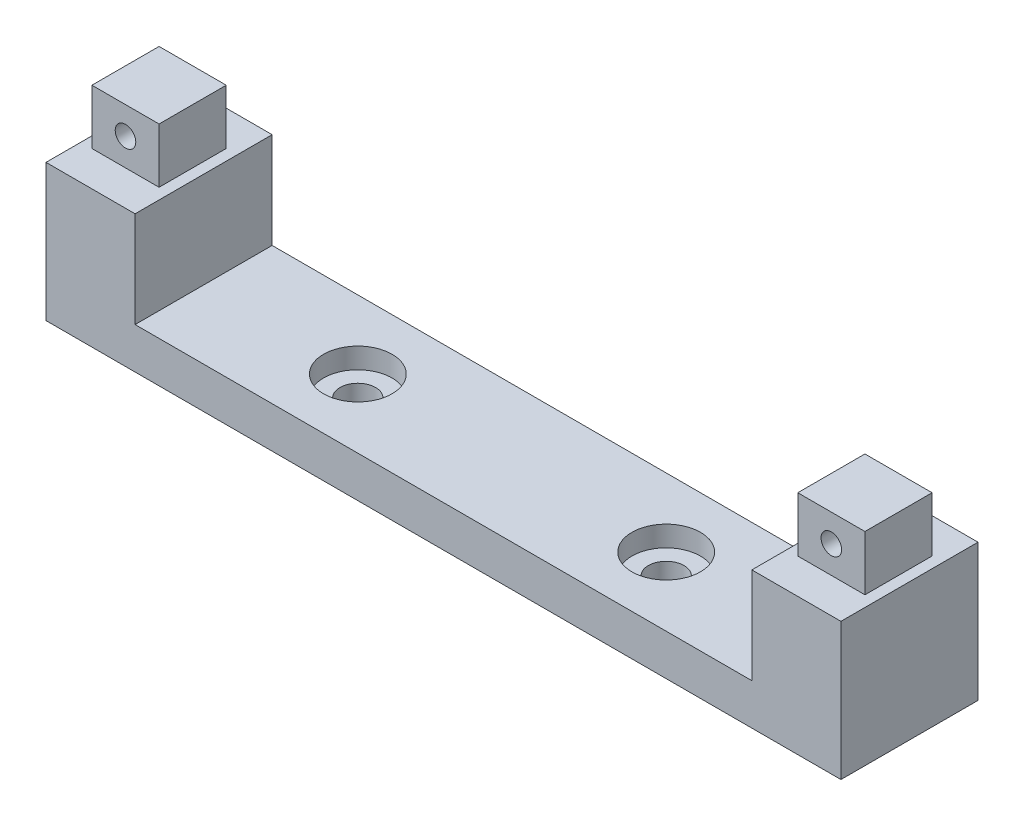
SolidWorks part; units mm, degrees
ref_plane "前视基准面" through (0, 0, 0) normal (0, 0, 1) x (1, 0, 0)
ref_plane "上视基准面" through (0, 0, 0) normal (0, 1, 0) x (1, 0, 0)
ref_plane "右视基准面" through (0, 0, 0) normal (1, 0, 0) x (0, 0, -1)
other "Configuration Table"
sketch "草图1" plane through (0, 0, 0) normal (0, 1, 0) x (1, 0, 0)
  line L1 (0, 0) -> (40, 0)
  line L2 (0, 0) -> (0, -20)
  line L3 (0, -20) -> (40, -20)
  line L4 (40, 0) -> (40, -20)
extrude "凸台-拉伸1" add sketch "草图1" along normal blind 6
sketch "草图5" plane through (0, 6, 0) normal (0, 1, 0) x (1, 0, 0)
  line L0 (0, -20) -> (40, -20) construction
  line L1 (0, 0) -> (33, 0)
  line L2 (0, 0) -> (0, -20)
  line L3 (0, -20) -> (33, -20)
  line L4 (33, 0) -> (33, -20)
  line L6 (33, 0) -> (40, 0)
  line L7 (33, 0) -> (33, -20)
  line L8 (33, -20) -> (40, -20)
  line L9 (40, 0) -> (40, -20)
  line M7 (0, -20) -> (40, -20)
  line M8 (40, -20) -> (40, 0)
  line M9 (40, 0) -> (0, 0)
extrude "切除-拉伸3" cut sketch "草图5" against normal blind 6 contours L4 M9 M7 M8
sketch "草图6" plane through (0, 6, 0) normal (0, 1, 0) x (1, 0, 0)
  line L0 (33, 0) -> (0, 0) construction
  line L1 (33, -20) -> (20, -20)
  line L2 (33, -20) -> (33, 0)
  line L3 (33, 0) -> (20, 0)
  line L4 (20, -20) -> (20, 0)
  line L6 (26.5, -10) -> (31.5, -10)
  line L7 (31.5, -10) -> (31.5, -5)
  line L8 (26.5, -10) -> (21.5, -10)
  line L9 (21.5, -10) -> (21.5, -15)
  line L10 (21.5, -15) -> (31.5, -15)
  line L11 (21.5, -15) -> (21.5, -5)
  line L12 (21.5, -5) -> (31.5, -5)
  line L13 (31.5, -15) -> (31.5, -5)
  line M14 (33, -20) -> (33, 0)
  line M15 (33, 0) -> (0, 0)
  line M17 (0, -20) -> (33, -20)
extrude "凸台-拉伸2" add sketch "草图6" along normal blind 20 contours L4 L13 L10 L9 L11 L12 L7 M17 M14 M15 | L12 L11 L8 L6 L7 | L10 L13 L6 L8 L9
sketch "草图8" plane through (0, 26, 0) normal (0, 1, 0) x (1, 0, 0)
  line L0 (20, 0) -> (33, -20)
  line L1 (26.5, -10) -> (31.4, -10)
  line L2 (31.4, -10) -> (31.4, -5.1)
  line L3 (26.5, -10) -> (21.6, -10)
  line L4 (21.6, -10) -> (21.6, -14.9)
  line L6 (21.6, -14.9) -> (31.4, -14.9)
  line L7 (21.6, -14.9) -> (21.6, -5.1)
  line L8 (21.6, -5.1) -> (31.4, -5.1)
  line L9 (31.4, -14.9) -> (31.4, -5.1)
extrude "凸台-拉伸3" add sketch "草图8" along normal blind 8 contours L8 L0 L1 L2 | L8 L7 L3 L0 | L4 L6 L0 L3 | L6 L9 L1 L0
sketch "草图9" plane through (0, 0, 14.9) normal (0, 0, 1) x (1, 0, 0)
  line L0 (26.5, 34) -> (26.5, 26)
  line L1 (21.6, 34) -> (31.4, 34) construction
  line L2 (21.6, 26) -> (31.4, 26) construction
  circle A0 centre (26.5, 30) radius 1.5
extrude "切除-拉伸4" cut sketch "草图9" against normal blind 10 contours L0 A0 | L0 A0
sketch "草图10" plane through (0, 0, 20) normal (0, 0, 1) x (1, 0, 0)
  line L0 (0, 0) -> (0, 6)
  line L1 (0, 6) -> (-70, 6)
  line L2 (-70, 26) -> (-83, 26)
  line L3 (-83, 26) -> (-83, 0)
  line L4 (-70, 6) -> (-70, 26)
  line L17 (-83, 0) -> (0, 0)
  circle A1 centre (-76.5, 30) radius 1.5
extrude "凸台-拉伸4" add sketch "草图10" against normal blind 20 contours L4 L2 L3 L17 L0 L1
sketch "草图12" plane through (0, 26, 0) normal (0, 1, 0) x (1, 0, 0)
  line L0 (-83, 0) -> (-70, -20)
  line L1 (-76.5, -10) -> (-71.6, -10)
  line L2 (-71.6, -10) -> (-71.6, -5.1)
  line L3 (-76.5, -10) -> (-81.4, -10)
  line L4 (-81.4, -10) -> (-81.4, -14.9)
  line L6 (-81.4, -14.9) -> (-71.6, -14.9)
  line L7 (-81.4, -14.9) -> (-81.4, -5.1)
  line L8 (-81.4, -5.1) -> (-71.6, -5.1)
  line L9 (-71.6, -14.9) -> (-71.6, -5.1)
extrude "凸台-拉伸5" add sketch "草图12" along normal blind 8 contours L8 L0 L1 L2 | L8 L7 L3 L0 | L4 L6 L0 L3 | L6 L9 L1 L0
sketch "草图13" plane through (0, 0, 14.9) normal (0, 0, 1) x (1, 0, 0)
  line L0 (-81.4, 34) -> (-71.6, 26)
  circle A0 centre (-76.5, 30) radius 1.5
extrude "切除-拉伸5" cut sketch "草图13" against normal blind 10 contours L0 A0 | L0 A0
sketch "草图15" plane through (0, 6, 0) normal (0, 1, 0) x (1, 0, 0)
  line L1 (-70, 0) -> (-70, -20) construction
  line L2 (20, -20) -> (20, 0) construction
  line L3 (-25, -10) -> (20, -10)
  line L4 (-25, -10) -> (-70, -10)
  circle A0 centre (-2.5, -10) radius 5
  circle A1 centre (-47.5, -10) radius 5
extrude "切除-拉伸6" cut sketch "草图15" against normal blind 3 contours L4 A1 | L4 A1 | L3 A0 | L3 A0
sketch "草图16" plane through (0, 3, 0) normal (0, 1, 0) x (1, 0, 0)
  circle A0 centre (-47.5, -10) radius 2.6
  circle A1 centre (-2.5, -10) radius 2.6
extrude "切除-拉伸7" cut sketch "草图16" against normal blind 3
sketch "草图18" plane through (0, 0, 0) normal (0, 0, -1) x (-1, 0, 0)
  line L0 (-20, 26) -> (-20, 6) construction
  line L1 (-33, 26) -> (-20, 26)
  line L2 (-33, 26) -> (-33, 6)
  line L3 (-33, 6) -> (-20, 6)
  line L4 (-20, 26) -> (-20, 6)
  line L6 (-33, 6) -> (83, 6)
  line L7 (-33, 6) -> (-33, 0)
  line L8 (-33, 0) -> (83, 0)
  line L9 (83, 6) -> (83, 0)
  line M2 (70, 6) -> (-20, 6)
  line M5 (-33, 26) -> (-33, 0)
  line M6 (-33, 0) -> (83, 0)
  line M7 (83, 0) -> (83, 26)
extrude "切除-拉伸8" cut sketch "草图18" against normal blind 20 contours L6 L3 M2 M5 M6 M7
sketch "草图19" plane through (0, 0, 0) normal (0, 0, -1) x (-1, 0, 0)
  line L0 (70, 6) -> (70, 26) construction
  line L1 (-20, 6) -> (70, 6)
  line L2 (-20, 6) -> (-20, 12)
  line L3 (-20, 12) -> (70, 12)
  line L4 (70, 6) -> (70, 12)
extrude "凸台-拉伸6" add sketch "草图19" against normal blind 20
sketch "草图20" plane through (0, 12, 0) normal (0, 1, 0) x (1, 0, 0)
  line L1 (-70, 0) -> (-70, -20) construction
  line L2 (20, -20) -> (20, 0) construction
  line L3 (-25, -10) -> (20, -10)
  line L4 (-25, -10) -> (-70, -10)
  circle A0 centre (-47.5, -10) radius 2.6
  circle A1 centre (-2.5, -10) radius 2.6
extrude "切除-拉伸9" cut sketch "草图20" against normal blind 20 contours L4 A0 | L4 A0 | L3 A1 | L3 A1
sketch "草图21" plane through (0, 12, 0) normal (0, 1, 0) x (1, 0, 0)
  circle A0 centre (-47.5, -10) radius 5
  circle A1 centre (-2.5, -10) radius 5
extrude "切除-拉伸10" cut sketch "草图21" against normal blind 3
